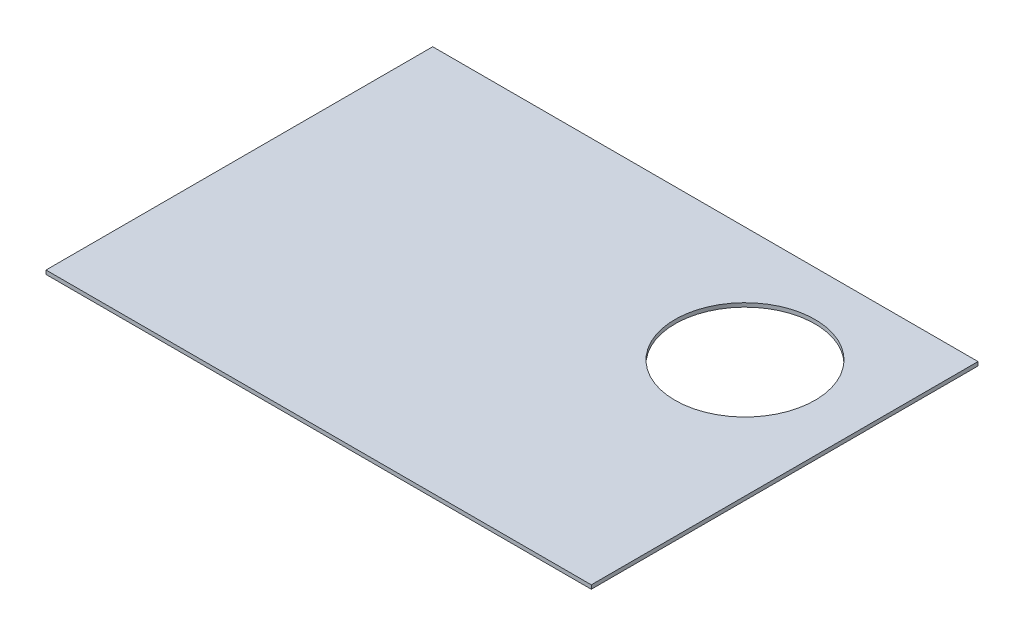
SolidWorks part; units mm, degrees
ref_plane "Front Plane" through (0, 0, 0) normal (0, 0, 1) x (1, 0, 0)
ref_plane "Top Plane" through (0, 0, 0) normal (0, 1, 0) x (1, 0, 0)
ref_plane "Right Plane" through (0, 0, 0) normal (1, 0, 0) x (0, 0, -1)
sketch "Sketch1" plane through (0, 0, 0) normal (0, 1, 0) x (1, 0, 0)
  line L0 (401.6375, 0) -> (447.675, 0)
  line L1 (0, 0) -> (46.0375, 0)
  line L2 (0, 0) -> (0, 317.5)
  line L3 (0, 317.5) -> (447.675, 317.5)
  line L4 (447.675, 0) -> (447.675, 317.5)
  line L6 (46.0375, 0) -> (46.0375, -3.175) construction
  line L7 (46.0375, -3.175) -> (401.6375, -3.175) construction
  line L8 (401.6375, 0) -> (401.6375, -3.175) construction
  line L9 (46.0375, 0) -> (401.6375, 0)
  point P9 (223.8375, -3.175)
  point P10 (223.8375, 317.5)
  dimension "D1" = 447.675
  dimension "D2" = 317.5
  dimension "D3" = 355.6
  dimension "D4" = 3.175
extrude "Boss-Extrude1" add sketch "Sketch1" along normal blind 3.175
ref_plane "Plane1" through (223.8375, 0, 0) normal (-1, 0, 0) x (0, 0, 1)
sketch "Sketch4" plane through (0, 3.175, 0) normal (0, 1, 0) x (1, 0, 0)
  line L0 (0, 0) -> (447.675, 0) construction
  line L1 (25.4, 314.325) -> (422.275, 314.325) construction
  line L2 (25.4, 314.325) -> (25.4, 0) construction
  line L3 (25.4, 0) -> (422.275, 0) construction
  line L4 (422.275, 314.325) -> (422.275, 0) construction
  line L6 (0, 317.5) -> (0, 0) construction
  line L7 (447.675, 0) -> (447.675, 317.5) construction
  line L8 (282.575, 0) -> (282.575, 314.325) construction
  line L9 (76.2, 314.325) -> (76.2, 0) construction
  line L10 (447.675, 317.5) -> (0, 317.5) construction
  circle A0 centre (282.575, 276.225) radius 1.5875
  circle A1 centre (76.2, 276.225) radius 1.5875
  dimension "D4" = 3.175
  dimension "D7" = 3.175
  dimension "D1" = 25.4
  dimension "D2" = 25.4
  dimension "D3" = 257.175
  dimension "D5" = 38.1
  dimension "D6" = 50.8
  dimension "D8" = 3.175
sketch "Sketch5" plane through (0, 3.175, 0) normal (0, 1, 0) x (1, 0, 0)
  line L1 (282.575, 314.325) -> (419.1, 314.325) construction
  line L2 (282.575, 314.325) -> (282.575, 0) construction
  line L3 (282.575, 0) -> (419.1, 0) construction
  line L4 (419.1, 314.325) -> (419.1, 0) construction
  line L5 (0, 0) -> (447.675, 0) construction
  line L6 (447.675, 0) -> (447.675, 317.5) construction
  line L7 (297.6562, 276.225) -> (404.0187, 276.225) construction
  line L8 (290.8375, 283.0438) -> (410.8375, 283.0437) construction
  line L9 (290.8375, 283.0438) -> (290.8375, 163.0437) construction
  line L10 (290.8375, 163.0437) -> (410.8375, 163.0437) construction
  line L11 (410.8375, 283.0437) -> (410.8375, 163.0437) construction
  line L12 (404.0187, 276.225) -> (404.0187, 169.8625) construction
  line L13 (297.6562, 276.225) -> (297.6562, 169.8625) construction
  line L14 (297.6562, 169.8625) -> (404.0187, 169.8625) construction
  line L15 (447.675, 317.5) -> (0, 317.5) construction
  circle A6 centre (350.8375, 223.0438) radius 57.5
  point P8 (0, 0)
  point P9 (0, 0)
  point P11 (350.8375, 314.325)
  point P18 (350.8375, 283.0438)
  point P27 (350.8375, 276.225)
  point P28 (404.0188, 223.0438)
  point P29 (410.8375, 223.0438)
  dimension "D8" = 115
  dimension "D1" = 28.575
  dimension "D2" = 120
  dimension "D4" = 106.3625
  dimension "D5" = 106.3625
  dimension "D6" = 3.175
extrude "Cut-Extrude4" cut sketch "Sketch5" against normal through all
